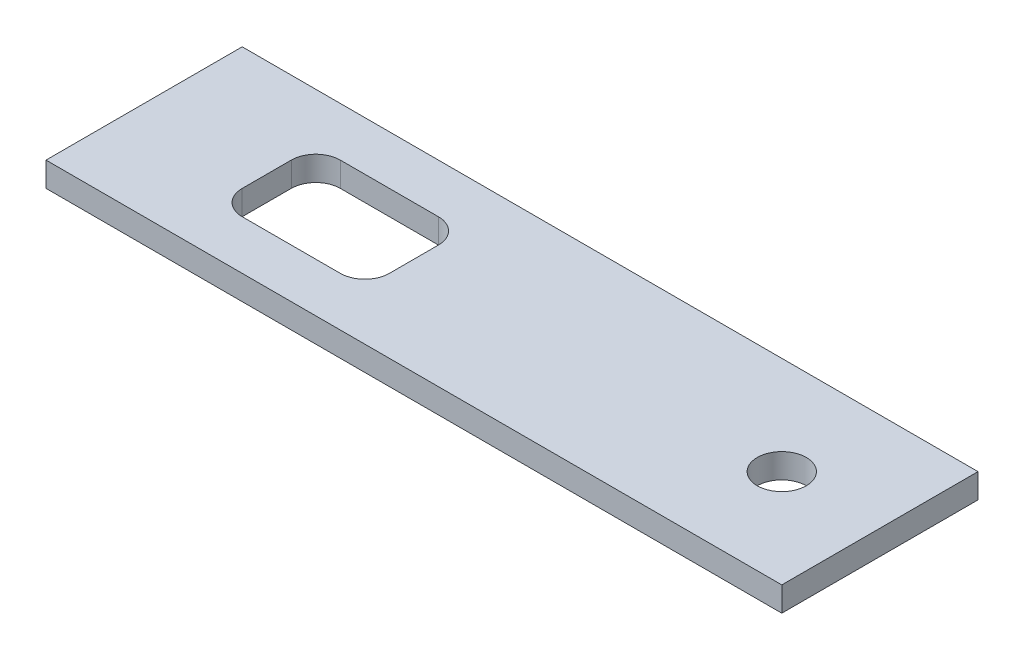
SolidWorks part; units mm, degrees
ref_plane "Front Plane" through (0, 0, 0) normal (0, 0, 1) x (1, 0, 0)
ref_plane "Top Plane" through (0, 0, 0) normal (0, 1, 0) x (1, 0, 0)
ref_plane "Right Plane" through (0, 0, 0) normal (1, 0, 0) x (0, 0, -1)
sketch "Sketch1" plane through (0, 0, 0) normal (0, 1, 0) x (1, 0, 0)
  line L1 (0, 0) -> (95.25, 0)
  line L2 (0, 0) -> (0, 25.4)
  line L3 (0, 25.4) -> (95.25, 25.4)
  line L4 (95.25, 0) -> (95.25, 25.4)
  line L5 (19.05, 19.05) -> (31.75, 19.05)
  line L6 (15.875, 15.875) -> (15.875, 9.525)
  line L7 (19.05, 6.35) -> (31.75, 6.35)
  line L8 (34.925, 15.875) -> (34.925, 9.525)
  line L9 (0, 25.4) -> (6.35, 25.4)
  line L10 (0, 25.4) -> (0, 20.6375)
  line L13 (0, 0) -> (6.35, 0)
  line L14 (0, 0) -> (0, 4.7625)
  line L17 (44.45, 0) -> (57.15, 0)
  line L21 (44.45, 25.4) -> (57.15, 25.4)
  arc A0 (34.925, 15.875) -> (31.75, 19.05) centre (31.75, 15.875) ccw
  arc A1 (19.05, 19.05) -> (15.875, 15.875) centre (19.05, 15.875) ccw
  arc A2 (31.75, 6.35) -> (34.925, 9.525) centre (31.75, 9.525) ccw
  arc A3 (19.05, 6.35) -> (15.875, 9.525) centre (19.05, 9.525) cw
  circle A5 centre (82.55, 12.7) radius 3.175
  point P9 (15.875, 12.7)
  point P10 (25.4, 19.05)
  point P13 (34.925, 19.05)
  point P16 (15.875, 19.05)
  point P19 (34.925, 6.35)
  point P23 (95.25, 12.7)
  dimension "D7" = 3.175
  dimension "D8" = 3.175
  dimension "D5" = 3.175
  dimension "D9" = 3.175
  dimension "D15" = 6.35
  dimension "D1" = 95.25
  dimension "D2" = 25.4
  dimension "D3" = 12.7
  dimension "D4" = 19.05
  dimension "D6" = 25.4
  dimension "D10" = 12.7
  dimension "D13" = 82.55
  dimension "D16" = 12.7
extrude "Boss-Extrude1" add sketch "Sketch1" along normal blind 3.175
